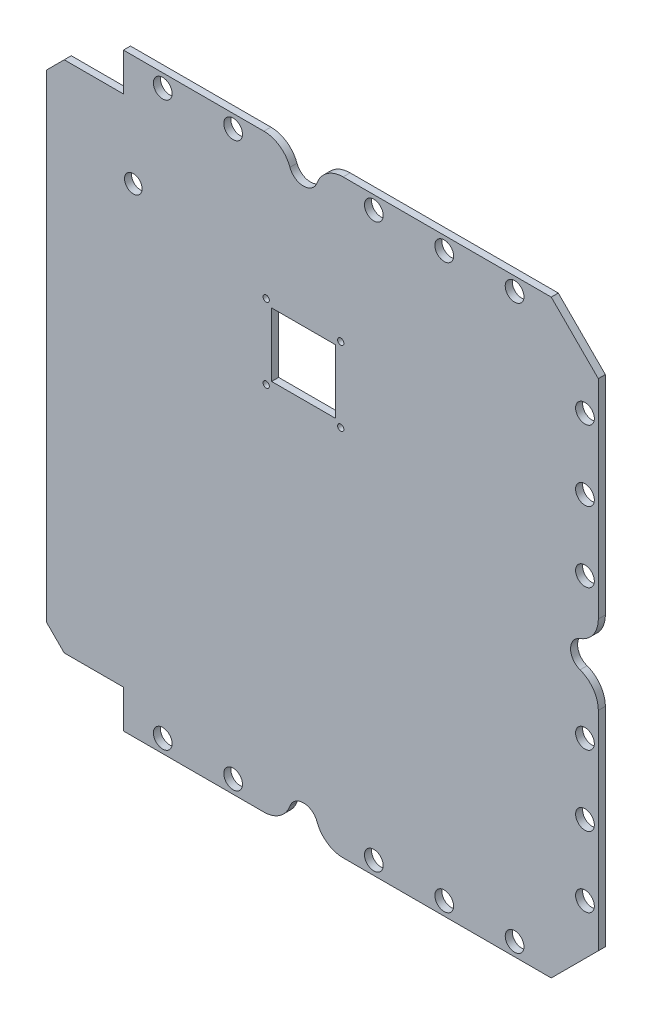
SolidWorks part; units mm, degrees
other "Markup1"
sketch "Sketch3" plane through (0, -212.852, 2.54) normal (0, 0, 1) x (1, 0, 0)
ref_plane "Front Plane" through (0, 0, 0) normal (0, 0, 1) x (1, 0, 0)
ref_plane "Top Plane" through (0, 0, 0) normal (0, 1, 0) x (1, 0, 0)
ref_plane "Right Plane" through (0, 0, 0) normal (1, 0, 0) x (0, 0, -1)
sketch "Sketch1" plane through (0, 0, 0) normal (0, 0, 1) x (1, 0, 0)
  line L0 (30.226, -4.826) -> (55.626, -4.826) construction
  line L5 (55.626, -4.826) -> (81.026, -4.826) construction
  line L6 (81.026, -4.826) -> (106.426, -4.826) construction
  line L7 (106.426, -4.826) -> (131.826, -4.826) construction
  line L8 (131.826, -4.826) -> (157.226, -4.826) construction
  line L9 (157.226, -4.826) -> (182.626, -4.826) construction
  line L10 (106.426, 0) -> (106.426, -212.852) construction
  line L11 (0, -106.426) -> (212.852, -106.426) construction
  line L12 (16.9978, 0) -> (0, -16.9979)
  line L13 (212.852, -16.9979) -> (195.8541, 0)
  line L14 (195.8541, -212.852) -> (212.852, -195.8542)
  line L15 (0, -195.8542) -> (16.9978, -212.852)
  line L16 (101.2317, 0) -> (101.2317, -4.826)
  line L17 (92.976, -51.8929) -> (119.876, -51.8929) construction
  line L18 (92.976, -51.8929) -> (92.976, -78.7929) construction
  line L19 (92.976, -78.7929) -> (119.876, -78.7929) construction
  line L20 (119.876, -51.8929) -> (119.876, -78.7929) construction
  line L21 (106.426, -78.7929) -> (106.426, -51.8929) construction
  line L22 (92.976, -65.3429) -> (119.876, -65.3429) construction
  line L23 (4.826, -111.6203) -> (0, -111.6203)
  line L24 (111.6203, -4.826) -> (111.6203, 0)
  line L25 (212.852, -101.2317) -> (208.026, -101.2317)
  line L26 (4.826, -101.2317) -> (0, -101.2317)
  line L27 (208.026, -111.6203) -> (212.852, -111.6203)
  line L28 (111.6203, -212.852) -> (111.6203, -208.026)
  line L29 (195.8541, 0) -> (111.6203, 0)
  line L30 (101.2317, -208.026) -> (101.2317, -212.852)
  line L31 (101.2317, 0) -> (16.9978, 0)
  line L32 (0, -16.9979) -> (0, -101.2317)
  line L33 (0, -111.6203) -> (0, -195.8542)
  line L34 (16.9978, -212.852) -> (101.2317, -212.852)
  line L35 (94.926, -53.8429) -> (117.926, -53.8429)
  line L36 (94.926, -53.8429) -> (94.926, -76.8429)
  line L37 (94.926, -76.8429) -> (117.926, -76.8429)
  line L38 (117.926, -53.8429) -> (117.926, -76.8429)
  line L39 (0, -111.6203) -> (4.826, -111.6203) [skipped]
  line L40 (4.826, -101.2317) -> (0, -101.2317) [skipped]
  line L41 (111.6203, -212.852) -> (195.8541, -212.852)
  line L42 (212.852, -195.8542) -> (212.852, -111.6203)
  line L43 (212.852, -101.2317) -> (212.852, -16.9979)
  line L44 (0, -16.9979) -> (212.852, -16.9979) construction
  line L45 (192.786, -13.716) -> (199.136, -20.066)
  line L46 (199.136, -20.066) -> (199.136, -192.786)
  line L47 (199.136, -192.786) -> (192.786, -199.136)
  line L48 (192.786, -199.136) -> (20.066, -199.136)
  line L49 (20.066, -199.136) -> (13.716, -192.786)
  line L50 (13.716, -192.786) -> (13.716, -20.066)
  line L51 (13.716, -20.066) -> (20.066, -13.716)
  line L52 (20.066, -13.716) -> (192.786, -13.716)
  line L53 (41.426, 0) -> (41.426, -13.716)
  line L54 (41.426, -199.136) -> (41.426, -212.852)
  circle A0 centre (30.226, -4.826) radius 3.38
  circle A1 centre (55.626, -4.826) radius 3.38
  circle A2 centre (81.026, -4.826) radius 3.38
  circle A3 centre (131.826, -4.826) radius 3.38
  circle A4 centre (157.226, -4.826) radius 3.38
  circle A5 centre (182.626, -4.826) radius 3.38
  circle A6 centre (106.426, -4.826) radius 5.1943
  circle A7 centre (208.026, -182.626) radius 3.38
  circle A8 centre (208.026, -157.226) radius 3.38
  circle A9 centre (208.026, -131.826) radius 3.38
  circle A10 centre (208.026, -106.426) radius 5.1943
  circle A11 centre (208.026, -81.026) radius 3.38
  circle A12 centre (208.026, -55.626) radius 3.38
  circle A13 centre (208.026, -30.226) radius 3.38
  circle A14 centre (30.226, -208.026) radius 3.38
  circle A15 centre (55.626, -208.026) radius 3.38
  circle A16 centre (81.026, -208.026) radius 3.38
  circle A17 centre (106.426, -208.026) radius 5.1943
  circle A18 centre (131.826, -208.026) radius 3.38
  circle A19 centre (157.226, -208.026) radius 3.38
  circle A20 centre (182.626, -208.026) radius 3.38
  circle A21 centre (4.826, -30.226) radius 3.38
  circle A22 centre (4.826, -55.626) radius 3.38
  circle A23 centre (4.826, -81.026) radius 3.38
  circle A24 centre (4.826, -106.426) radius 5.1943
  circle A25 centre (4.826, -131.826) radius 3.38
  circle A26 centre (4.826, -157.226) radius 3.38
  circle A27 centre (4.826, -182.626) radius 3.38
  circle A29 centre (92.976, -51.8929) radius 1.13
  circle A30 centre (119.876, -51.8929) radius 1.13
  circle A31 centre (119.876, -78.7929) radius 1.13
  circle A32 centre (92.976, -78.7929) radius 1.13
  circle A33 centre (45, -40) radius 3.175
  circle A34 centre (106.426, -65.3429) radius 7.4189 construction
  point P14 (106.426, -106.426)
  point P69 (106.426, -106.426)
  point P78 (106.426, -106.426)
  point P104 (106.426, -106.426)
  point P107 (106.426, -53.8429)
  point P108 (117.926, -65.3429)
  dimension "D1" = 6.76
  dimension "D5" = 10.3886
  dimension "D14" = 2.26
  dimension "D19" = 6.35
  dimension "D2" = 4.826
  dimension "D3" = 25.4
  dimension "D4" = 4.826
  dimension "D6" = 212.852
  dimension "D7" = 65
  dimension "D10" = 24.0386
  dimension "D12" = 23
  dimension "D15" = 26.9
  dimension "D8" = 4
  dimension "D11" = 4
  dimension "D18" = 4
extrude "Boss-Extrude1" add sketch "Sketch1" along normal blind 2.54 contours A17 L28 L41 L14 L42 L27 A10 L25 L43 L13 L29 L24 A6 L16 L31 L53 L52 L45 L46 L47 L48 L54 L34 L30 A20 A19 A18 A1 A2 A3 A4 A5 A7 A8 A9 A11 A12 | L52 L51 L50 L49 L48 L47 L46 L45 A33 A32 A31 A30 A29 L35 L38 L37 L36
hole_wizard "#4-40 Tapped Hole1" positions "3DSketch1" profile "Sketch2" tap size "#4-40" standard "ANSI Inch" end condition through all
sketch3d "3DSketch1"
  line L0 (92.976, -51.8929, 2.54) -> (92.976, -51.8929, 0) construction
  line L1 (119.876, -51.8929, 2.54) -> (119.876, -51.8929, 0) construction
  line L2 (119.876, -78.7929, 2.54) -> (119.876, -78.7929, 0) construction
  line L3 (92.976, -78.7929, 2.54) -> (92.976, -78.7929, 0) construction
  point P0 (92.976, -51.8929, 2.54)
  point P4 (119.876, -51.8929, 2.54)
  point P8 (119.876, -78.7929, 2.54)
  point P12 (92.976, -78.7929, 2.54)
sketch "Sketch2" plane through (92.976, -51.8929, 2.54) normal (1, 0, 0) x (0, -1, 0)
  line L0 (0, 0) -> (0, 2.54)
  line L1 (0, 2.54) -> (1.1303, 2.54)
  line L2 (1.1303, 2.54) -> (1.1303, 0)
  line L5 (1.1303, 0) -> (0, 0)
  line L11 (0, -6.35) -> (0, 107.95) construction
  dimension "Thru Tap Drill Dia." = 2.2606
  dimension "Thru Tap Drill Depth" = 2.54
cosmetic thread "Hole Thread1" parameters "D2"=2.8448
cosmetic thread "Hole Thread2" parameters "D2"=2.8448
cosmetic thread "Hole Thread3" parameters "D2"=2.8448
cosmetic thread "Hole Thread4" parameters "D2"=2.8448
fillet "Fillet1" radius 10 6 edges at (101.2317, -212.852, 1.27) (111.6203, -212.852, 1.27) (212.852, -111.6203, 1.27) (212.852, -101.2317, 1.27) (111.6203, 0, 1.27) (101.2317, 0, 1.27)
